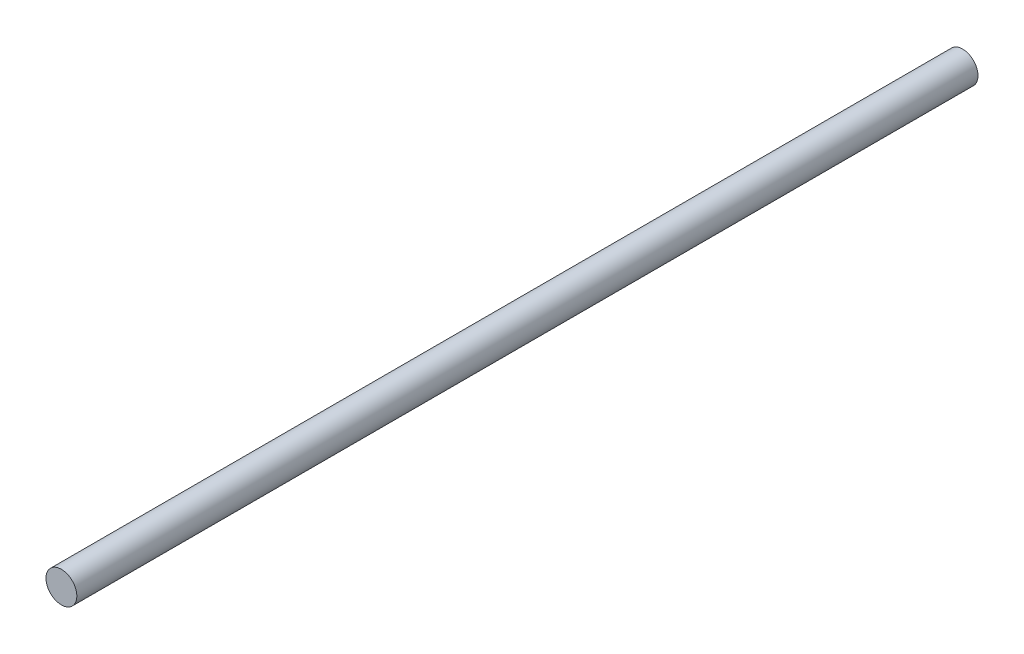
SolidWorks part; units mm, degrees
ref_plane "Ön Düzlem" through (0, 0, 0) normal (0, 0, 1) x (1, 0, 0)
ref_plane "Üst Düzlem" through (0, 0, 0) normal (0, 1, 0) x (1, 0, 0)
ref_plane "Sağ Düzlem" through (0, 0, 0) normal (1, 0, 0) x (0, 0, -1)
sketch "Sketch1" plane through (0, 0, 0) normal (0, 0, 1) x (1, 0, 0)
  circle A0 centre (0, 0) radius 5
extrude "Boss-Extrude1" add sketch "Sketch1" along normal blind 292
